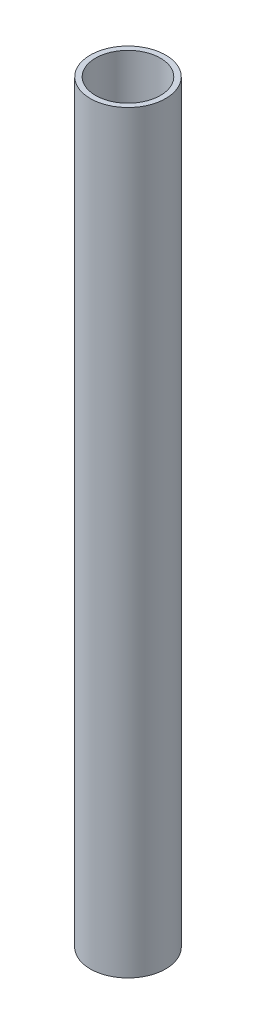
SolidWorks part; units mm, degrees
material "AISI 316 Stainless Steel Sheet (SS)"
ref_plane "Front Plane" through (0, 0, 0) normal (0, 0, 1) x (1, 0, 0)
ref_plane "Top Plane" through (0, 0, 0) normal (0, 1, 0) x (1, 0, 0)
ref_plane "Right Plane" through (0, 0, 0) normal (1, 0, 0) x (0, 0, -1)
sketch "Sketch1" plane through (0, 0, 0) normal (0, 1, 0) x (1, 0, 0)
  circle A0 centre (0, 0) radius 6.35
  dimension "D1" = 12.7
extrude "Boss-Extrude1" add sketch "Sketch1" along normal blind 127
sketch "Sketch2" plane through (0, 127, 0) normal (0, 1, 0) x (1, 0, 0)
  circle A0 centre (0, 0) radius 5.461
  dimension "D1" = 10.922
extrude "Cut-Extrude3" cut sketch "Sketch2" against normal blind 127
